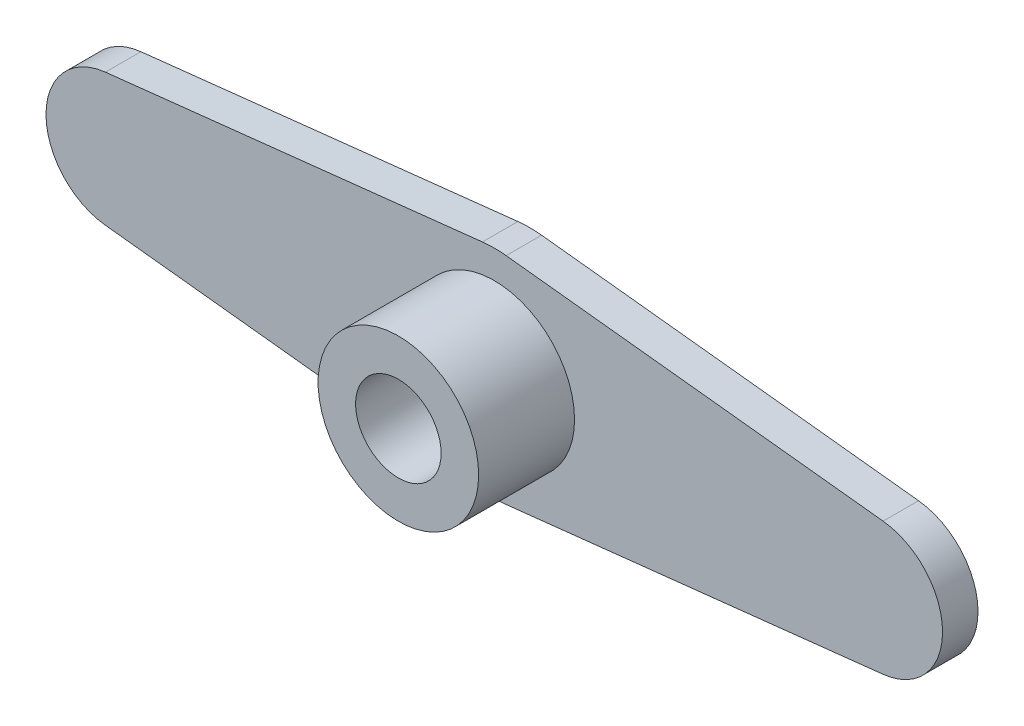
SolidWorks part; units mm, degrees
ref_plane "Front Plane" through (0, 0, 0) normal (0, 0, 1) x (1, 0, 0)
ref_plane "Top Plane" through (0, 0, 0) normal (0, 1, 0) x (1, 0, 0)
ref_plane "Right Plane" through (0, 0, 0) normal (1, 0, 0) x (0, 0, -1)
sketch "Sketch1" plane through (0, 0, 0) normal (0, 0, 1) x (1, 0, 0)
  line L0 (-23.241, 0) -> (23.241, 0) construction
  line L1 (-23.6852, 4.0397) -> (-0.7217, 6.5644)
  line L2 (0.7217, 6.5644) -> (23.6852, 4.0397)
  line L3 (23.6852, -4.0397) -> (0.7217, -6.5644)
  line L4 (-23.6852, -4.0397) -> (-0.7217, -6.5644)
  arc A0 (-0.7217, -6.5644) -> (0.7217, -6.5644) centre (0, 0) ccw
  arc A1 (-23.6852, 4.0397) -> (-23.6852, -4.0397) centre (-23.241, 0) ccw
  arc A2 (23.6852, -4.0397) -> (23.6852, 4.0397) centre (23.241, 0) ccw
  arc A3 (0.7217, 6.5644) -> (-0.7217, 6.5644) centre (0, 0) ccw
  point P1 (-27.305, 0)
  point P4 (27.305, 0)
  dimension "D1" = 8.128
  dimension "D2" = 13.208
  dimension "D3" = 54.61
extrude "Boss-Extrude1" add sketch "Sketch1" along normal blind 2.159 contours L1 A3 L2 A2 L3 A0 L4 A1
sketch "Sketch2" plane through (0, 0, 2.159) normal (0, 0, 1) x (1, 0, 0)
  circle A0 centre (0, 0) radius 4.8895
  circle A1 centre (0, 0) radius 2.6035
  dimension "D1" = 9.779
  dimension "D2" = 2.286
extrude "Boss-Extrude2" add sketch "Sketch2" along normal blind 5.842
